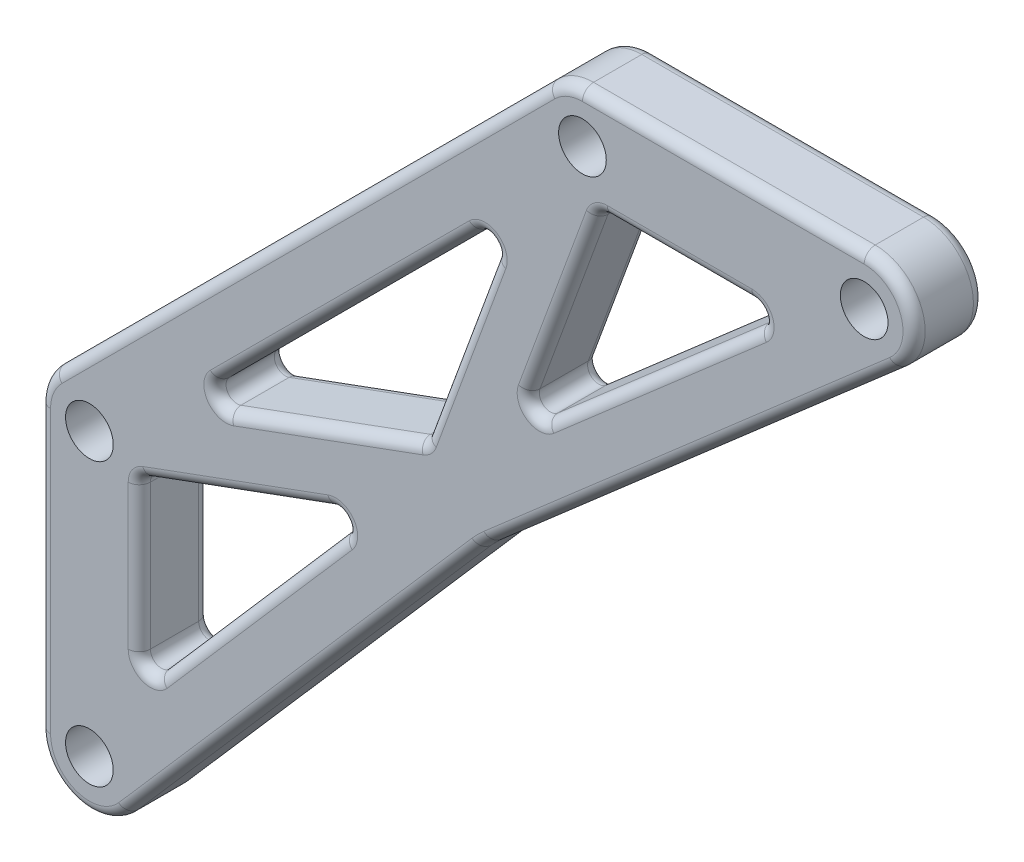
SolidWorks part; units mm, degrees
ref_plane "Front Plane" through (0, 0, 0) normal (0, 0, 1) x (1, 0, 0)
ref_plane "Top Plane" through (0, 0, 0) normal (0, 1, 0) x (1, 0, 0)
ref_plane "Right Plane" through (0, 0, 0) normal (1, 0, 0) x (0, 0, -1)
sketch "Sketch1" plane through (0, 0, 0) normal (0, 0, 1) x (1, 0, 0)
  line L0 (0, 0) -> (0, 25.4) construction
  line L1 (0, 25.4) -> (44.45, 69.85) construction
  line L2 (44.45, 69.85) -> (69.85, 69.85) construction
  line L3 (0, 25.4) -> (32.5134, 37.3366) construction
  line L4 (32.5134, 37.3366) -> (44.45, 69.85) construction
  line L5 (32.5134, 37.3366) -> (69.85, 69.85) construction
  line L6 (0, 0) -> (32.5134, 37.3366) construction
  line L7 (4.5, 23.8563) -> (4.5, 7.4516)
  line L8 (4.5, 7.4516) -> (25.4989, 31.5656)
  line L9 (25.4989, 31.5656) -> (4.5, 23.8563)
  line L10 (8.4016, 31.6802) -> (30.1758, 39.6742)
  line L11 (30.1758, 39.6742) -> (38.1698, 61.4484)
  line L12 (38.1698, 61.4484) -> (8.4016, 31.6802)
  line L13 (45.9937, 65.35) -> (38.2844, 44.3511)
  line L14 (38.2844, 44.3511) -> (62.3984, 65.35)
  line L15 (62.3984, 65.35) -> (45.9937, 65.35)
  line L16 (-4.5, 25.4) -> (-4.5, 0)
  line L17 (3.3936, -2.9552) -> (35.703, 34.147)
  line L18 (72.8052, 66.4564) -> (35.703, 34.147)
  line L19 (32.5134, 37.3366) -> (35.703, 34.147) construction
  line L20 (-3.182, 28.582) -> (41.268, 73.032)
  line L21 (44.45, 74.35) -> (69.85, 74.35)
  circle A0 centre (0, 0) radius 2.15
  circle A1 centre (0, 25.4) radius 2.15
  circle A2 centre (44.45, 69.85) radius 2.15
  circle A3 centre (69.85, 69.85) radius 2.15
  circle A6 centre (0, 25.4) radius 4.5
  circle A7 centre (44.45, 69.85) radius 4.5
  circle A8 centre (69.85, 69.85) radius 4.5
  circle A9 centre (0, 0) radius 4.5
  point P9 (19.043, 50.807)
  dimension "D5" = 4.3
  dimension "D7" = 9
  dimension "D1" = 25.4
  dimension "D2" = 25.4
  dimension "D3" = 44.45
  dimension "D4" = 44.45
  dimension "D6" = 19.05
  dimension "D8" = 9
  dimension "D9" = 6
  dimension "D10" = 6
  dimension "D11" = 6
  dimension "D12" = 6
  dimension "D13" = 6
  dimension "D14" = 9
  dimension "D15" = 6
  dimension "D16" = 6
extrude "Boss-Extrude1" add sketch "Sketch1" along normal blind 6.35
fillet "Fillet1" radius 1 9 edges at (62.3984, 65.35, 3.175) (38.2844, 44.3511, 3.175) (45.9937, 65.35, 3.175) (30.1758, 39.6742, 3.175) (38.1698, 61.4484, 3.175) (8.4016, 31.6802, 3.175) (25.4989, 31.5656, 3.175) (4.5, 7.4516, 3.175) (4.5, 23.8563, 3.175)
fillet "Fillet2" radius 10 1 edges at (35.703, 34.147, 3.175)
fillet "Fillet3" radius 1 56 edges at (23.0097, 29.8513, 6.35) (23.0097, 29.8513, 0) (14.5972, 19.0467, 6.35) (14.5972, 19.0467, 0) (5.1494, 9.1862, 6.35) (5.1494, 9.1862, 0) (4.5, 16.6404, 6.35) (4.5, 16.6404, 0) (4.68, 23.7306, 6.35) (4.68, 23.7306, 0) (30.1037, 39.7463, 6.35) (30.1037, 39.7463, 0) (21.2026, 36.3799, 6.35) (21.2026, 36.3799, 0) (11.4767, 33.6454, 6.35) (11.4767, 33.6454, 0) (23.2857, 46.5643, 0) (23.2857, 46.5643, 6.35) (36.2046, 58.3733, 6.35) (36.2046, 58.3733, 0) (39.9987, 46.8403, 6.35) (39.9987, 46.8403, 0) (42.6901, 56.3516, 6.35) (42.6901, 56.3516, 0) (46.1194, 65.17, 6.35) (46.1194, 65.17, 0) (53.2096, 65.35, 0) (53.2096, 65.35, 6.35) (60.6638, 64.7006, 6.35) (60.6638, 64.7006, 0) (74.0643, 71.4278, 0) (74.0643, 71.4278, 6.35) (57.15, 74.35, 0) (57.15, 74.35, 6.35) (42.7279, 74.0075, 0) (42.7279, 74.0075, 6.35) (19.043, 50.807, 0) (19.043, 50.807, 6.35) (-4.1575, 27.1221, 0) (-4.1575, 27.1221, 6.35) (-4.5, 12.7, 0) (-4.5, 12.7, 6.35) (-1.5778, -4.2143, 0) (-1.5778, -4.2143, 6.35) (19.3216, 15.3355, 0) (19.3216, 15.3355, 6.35) (35.7198, 34.1302, 6.35) (35.7198, 34.1302, 0) (50.8033, 55.2528, 6.35) (50.8033, 55.2528, 0) (33.4701, 48.6474, 0) (33.4701, 48.6474, 6.35) (54.5145, 50.5284, 6.35) (54.5145, 50.5284, 0) (13.4984, 27.1599, 0) (13.4984, 27.1599, 6.35)
